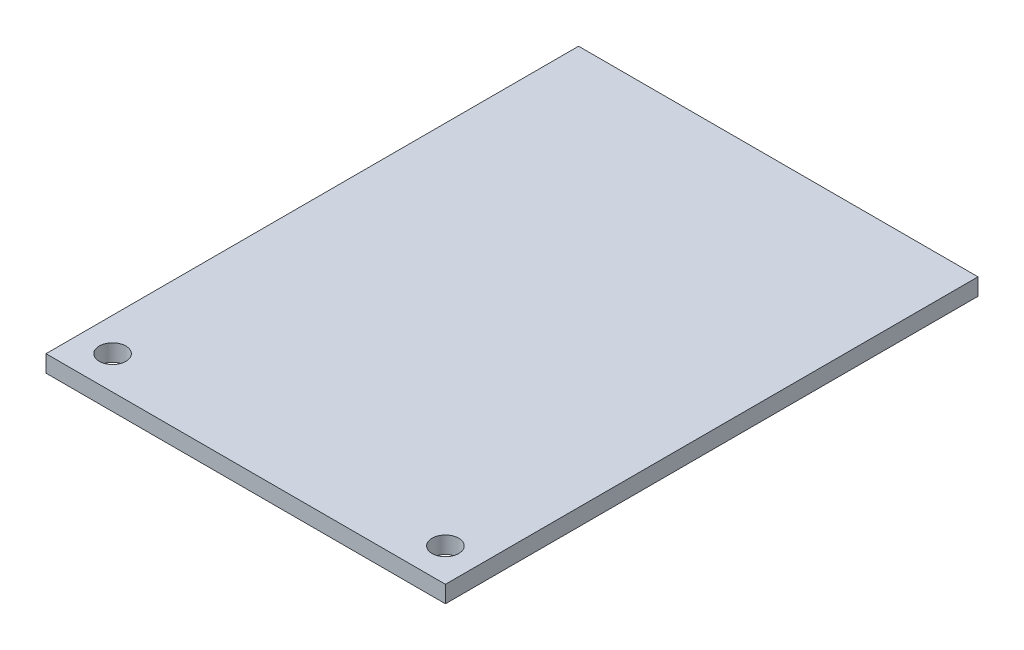
SolidWorks part; units mm, degrees
ref_plane "Front Plane" through (0, 0, 0) normal (0, 0, 1) x (1, 0, 0)
ref_plane "Top Plane" through (0, 0, 0) normal (0, 1, 0) x (1, 0, 0)
ref_plane "Right Plane" through (0, 0, 0) normal (1, 0, 0) x (0, 0, -1)
sketch "Sketch1" plane through (0, 0, 0) normal (0, 1, 0) x (1, 0, 0)
  line L1 (-30, 40) -> (30, 40)
  line L2 (-30, 40) -> (-30, -40)
  line L3 (-30, -40) -> (30, -40)
  line L4 (30, 40) -> (30, -40)
  line L5 (-30, 40) -> (30, -40) construction
  line L6 (-30, -40) -> (30, 40) construction
  point P0 (0, 0)
  dimension "D1" = 60
  dimension "D2" = 80
extrude "Boss-Extrude1" add sketch "Sketch1" along normal blind 2.54
sketch "Sketch3" plane through (0, 2.54, 0) normal (0, 1, 0) x (1, 0, 0)
  line L0 (-30, -35) -> (30, -35) construction
  line L1 (-30, 40) -> (-30, -40) construction
  line L2 (30, -40) -> (30, 40) construction
  line L3 (-30, -40) -> (30, -40) construction
  circle A0 centre (-25, -35) radius 2
  point P10 (0, 0)
  dimension "D2" = 4
  dimension "D1" = 5
  dimension "D3" = 5
extrude "Cut-Extrude1" cut sketch "Sketch3" against normal through all
mirror "Mirror1" about plane through (0, 0, 0) normal (1, 0, 0) of "Cut-Extrude1"
